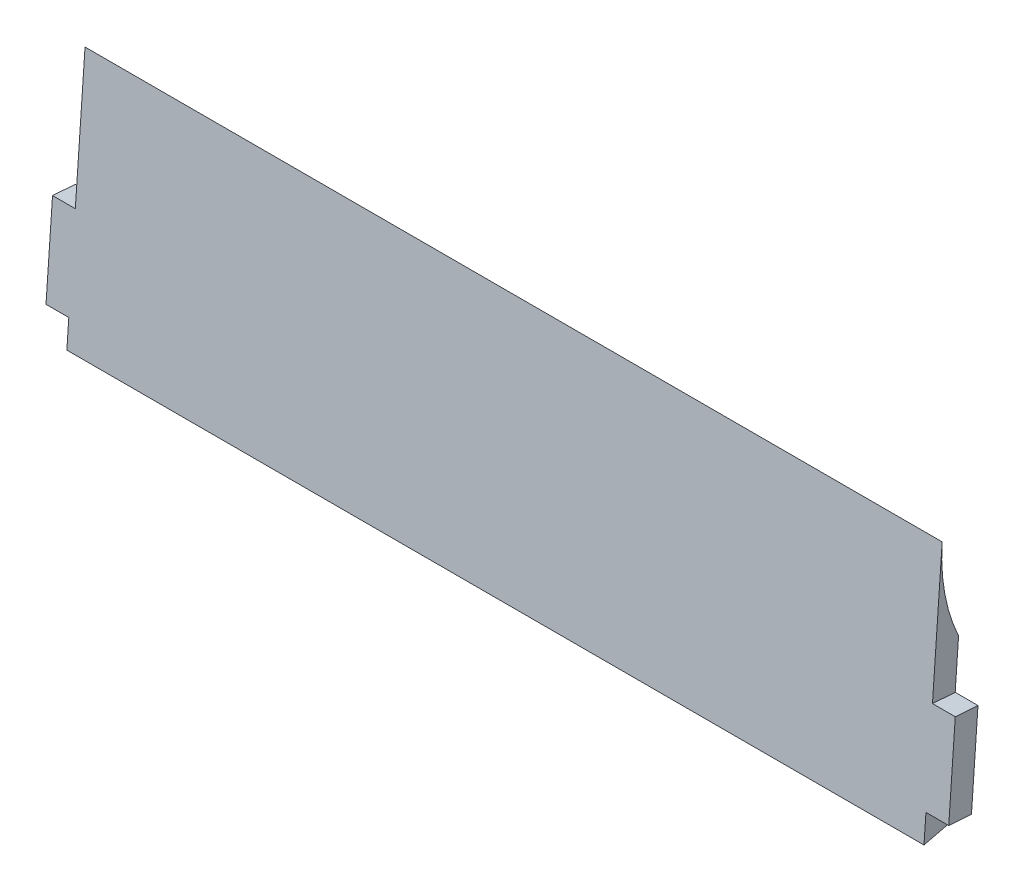
SolidWorks part; units mm, degrees
material "AISI 4130 Steel, annealed at 865C"
ref_plane "X-Y Datum" through (0, 0, 0) normal (0, 0, 1) x (1, 0, 0)
ref_plane "X-Z Datum" through (0, 0, 0) normal (0, 1, 0) x (1, 0, 0)
ref_plane "Y-Z Datum" through (0, 0, 0) normal (1, 0, 0) x (0, 0, -1)
sketch "Sketch1" plane through (0, 0, 0) normal (1, 0, 0) x (0, 0, -1)
  line L0 (0.5909, -4.4662) -> (0.1364, -10.7999)
  line L1 (0.5909, -4.4662) -> (2.1743, -4.5798) construction
  line L4 (1.7198, -10.9135) -> (2.1743, -4.5798) construction
  line L5 (0, -12.7) -> (0.1364, -10.7999) construction
  line L6 (0.1364, -10.7999) -> (0, -12.7)
  line L7 (0, -12.7) -> (1.6199, -12.3057)
  line L8 (1.6199, -12.3057) -> (2.1743, -4.5798)
  line L9 (0.5909, -4.4662) -> (1.2665, 4.9492)
  line L10 (2.1743, -4.5798) -> (2.4099, -1.297)
  line L11 (1.5425, -12.3245) -> (0, -12.7) construction
  arc A1 (2.4099, -1.297) -> (1.2665, 4.9492) centre (13.934, 4.0402) cw
  circle A2 centre (13.934, 4.0402) radius 12.7 construction
  dimension "D1" = 25.4
  dimension "D2" = 6.35
  dimension "D3" = 1.5875
extrude "Boss-Extrude1" add sketch "Sketch1" along normal blind 59.69
sketch "Sketch2" plane through (0, -0.0651, -0.9067) normal (0, 0.0716, 0.9974) x (1, 0, 0)
  line L0 (0, 5.0272) -> (0, -12.6674) construction
  line L1 (-1.5875, -4.4124) -> (0, -4.4124)
  line L2 (-1.5875, -4.4124) -> (-1.5875, -10.7624)
  line L3 (-1.5875, -10.7624) -> (0, -10.7624)
  line L4 (0, -4.4124) -> (0, -10.7624)
  line L5 (29.845, -12.6674) -> (29.845, 5.0272) construction
  line L12 (-1.5875, -10.7624) -> (0, -10.7624) construction
  line L13 (59.69, -12.6674) -> (0, -12.6674) construction
  line L14 (59.69, 5.0272) -> (0, 5.0272) construction
  line L15 (61.2775, -10.7624) -> (59.69, -10.7624)
  line L16 (61.2775, -4.4124) -> (61.2775, -10.7624)
  line L17 (59.69, -4.4124) -> (59.69, -10.7624)
  line L18 (61.2775, -4.4124) -> (59.69, -4.4124)
  dimension "D1" = 6.35
  dimension "D2" = 1.5875
extrude "Boss-Extrude2" add sketch "Sketch2" against normal up to surface (1.5875 mm away)
